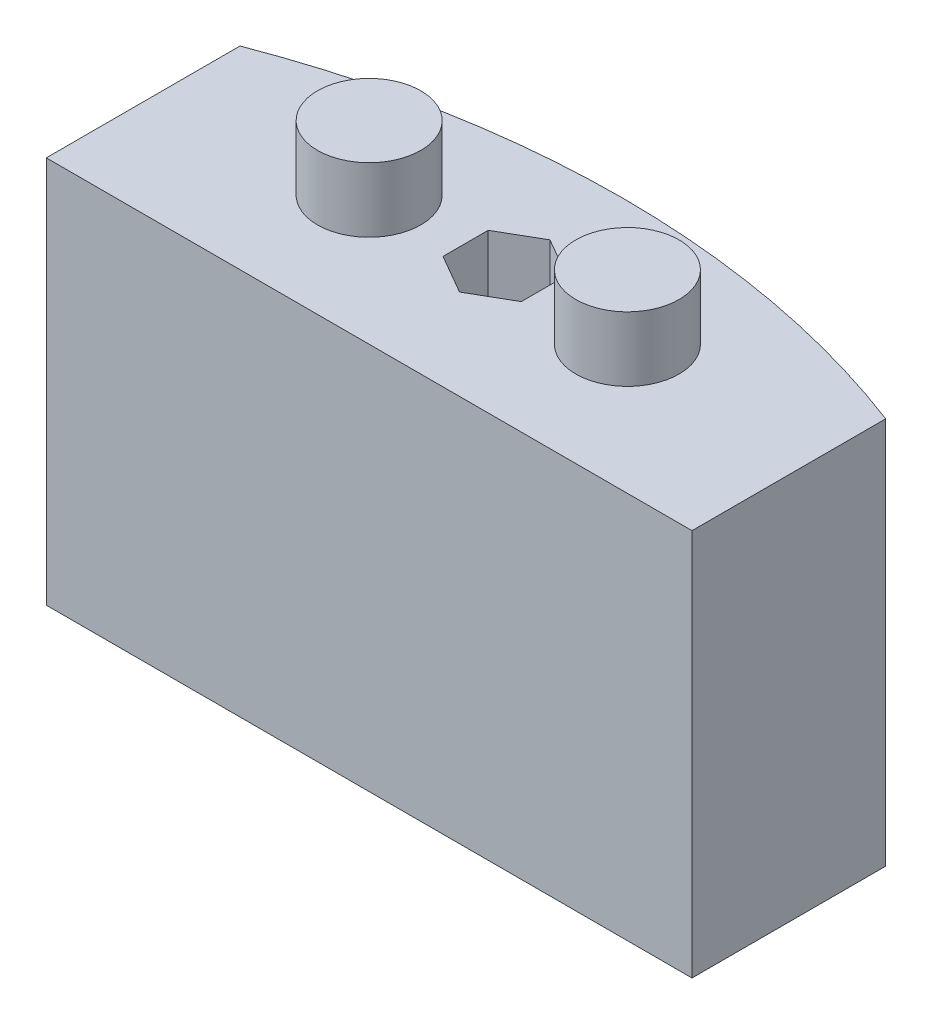
SolidWorks part; units mm, degrees
material "ABS"
ref_plane "Front Plane" through (0, 0, 0) normal (0, 0, 1) x (1, 0, 0)
ref_plane "Top Plane" through (0, 0, 0) normal (0, 1, 0) x (1, 0, 0)
ref_plane "Right Plane" through (0, 0, 0) normal (1, 0, 0) x (0, 0, -1)
sketch "Sketch1" plane through (0, 0, 0) normal (0, 1, 0) x (1, 0, 0)
  line L0 (-25, 0) -> (25, 0)
  line L1 (25, 0) -> (25, 15)
  line L2 (-25, 0) -> (-25, 15)
  circle A1 centre (0, -50.3835) radius 70
  arc A2 (-25, 15) -> (25.1901, 14.927) centre (0, -50.3835) cw
  point P6 (0, 0)
  dimension "D1" = 140
  dimension "D2" = 50
  dimension "D3" = 15
extrude "Boss-Extrude1" add sketch "Sketch1" along normal blind 30 contours L1 A1 L2 L0
sketch "Sketch2" plane through (0, 30, 0) normal (0, 1, 0) x (1, 0, 0)
  line L1 (-10, 10) -> (10, 10) construction
  line L2 (-25, 0) -> (25, 0) construction
  circle A0 centre (-10, 10) radius 4
  circle A1 centre (10, 10) radius 4
  point P4 (0, 10)
  point P7 (0, 0)
  dimension "D1" = 8
  dimension "D2" = 8
  dimension "D3" = 20
  dimension "D4" = 10
extrude "Boss-Extrude2" add sketch "Sketch2" along normal blind 5
sketch "Sketch3" plane through (0, 30, 0) normal (0, -1, 0) x (1, 0, 0)
  line L1 (0, -7) -> (-3.0311, -8.75)
  line L2 (-3.0311, -8.75) -> (-3.0311, -12.25)
  line L3 (-3.0311, -12.25) -> (0, -14)
  line L4 (0, -14) -> (3.0311, -12.25)
  line L5 (3.0311, -12.25) -> (3.0311, -8.75)
  line L6 (3.0311, -8.75) -> (0, -7)
  line L11 (25, 0) -> (25, -15) construction
  circle A0 centre (0, -10.5) radius 3.0311 construction
  point P17 (25, -7.5)
  dimension "D1" = 3.5
  dimension "D2" = 3
extrude "Cut-Extrude1" cut sketch "Sketch3" along normal blind 27
sketch "Sketch4" plane through (0, 0, 0) normal (0, -1, 0) x (1, 0, 0)
  circle A0 centre (0, -10.5) radius 1.25
  dimension "D2" = 2.5
  dimension "D1" = 3.5
extrude "Cut-Extrude2" cut sketch "Sketch4" against normal blind 10
